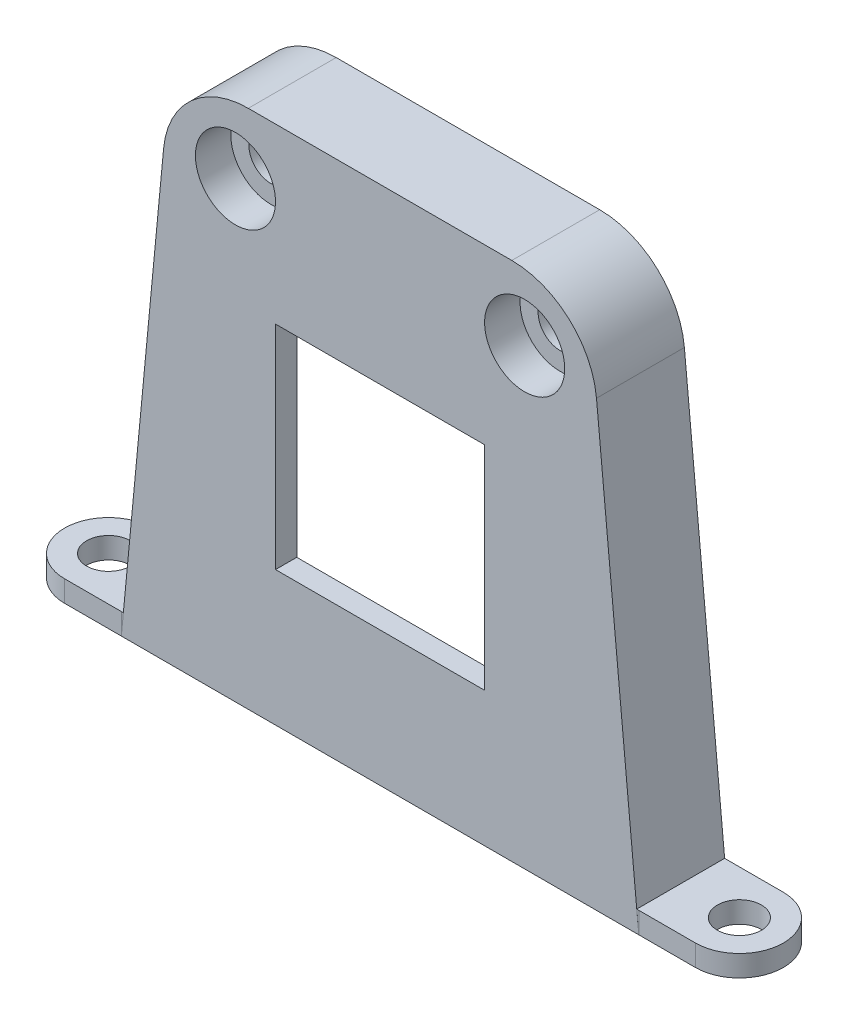
SolidWorks part; units mm, degrees
ref_plane "Přední rovina" through (0, 0, 0) normal (0, 0, 1) x (1, 0, 0)
ref_plane "Horní rovina" through (0, 0, 0) normal (0, 1, 0) x (1, 0, 0)
ref_plane "Pravá rovina" through (0, 0, 0) normal (1, 0, 0) x (0, 0, -1)
sketch "Sketch1" plane through (0, 0, 0) normal (0, 0, 1) x (1, 0, 0)
  line L0 (-12.25, 17.11) -> (12.25, -17.11) construction
  line L16 (18.25, -17.11) -> (15.2676, 14.1793)
  line L17 (9.2947, 19.61) -> (-9.2947, 19.61)
  line L18 (-15.2676, 14.1793) -> (-18.25, -17.11)
  line L19 (-18.25, -17.11) -> (-12.25, -17.11)
  line L20 (-12.25, -17.11) -> (-12.25, 17.11)
  line L21 (-12.25, 17.11) -> (12.25, 17.11)
  line L22 (12.25, 17.11) -> (12.25, -17.11)
  line L23 (12.25, -17.11) -> (18.25, -17.11)
  arc A4 (15.2676, 14.1793) -> (9.2947, 19.61) centre (9.2947, 13.61) ccw
  arc A5 (-9.2947, 19.61) -> (-15.2676, 14.1793) centre (-9.2947, 13.61) ccw
  dimension "D8" = 6
  dimension "D9" = 6
  dimension "D1" = 6
  dimension "D2" = 6
  dimension "D3" = 2.9553
  dimension "D4" = 2.9553
  dimension "D5" = 34.22
  dimension "D6" = 34.22
  dimension "D7" = 42.0863
  dimension "D10" = 2.5
  dimension "D11" = 2.9307
  dimension "D12" = 2.9307
  dimension "D13" = 3.0176
  dimension "D14" = 3.0176
extrude "Boss-Extrude1" add sketch "Sketch1" along normal blind 4.7
sketch "Sketch2" plane through (0, 0, 4.7) normal (0, 0, 1) x (1, 0, 0)
  line L1 (-12.25, -17.11) -> (12.25, -17.11)
  line L2 (-12.25, -17.11) -> (-12.25, 17.11)
  line L3 (-12.25, 17.11) -> (12.25, 17.11)
  line L4 (12.25, -17.11) -> (12.25, 17.11)
  line L5 (-12.25, -17.11) -> (12.25, 17.11) construction
  line L6 (-12.25, 17.11) -> (12.25, -17.11) construction
  line L7 (-7.375, 7.39) -> (7.375, 7.39)
  line L8 (12.25, -17.11) -> (18.25, -17.11)
  line L9 (18.25, -17.11) -> (15.2676, 14.1793)
  line L10 (9.2947, 19.61) -> (-9.2947, 19.61)
  line L11 (-15.2676, 14.1793) -> (-18.25, -17.11)
  line L12 (-18.25, -17.11) -> (-12.25, -17.11)
  line L13 (-12.25, -17.11) -> (-12.25, 17.11)
  line L14 (-12.25, 17.11) -> (12.25, 17.11)
  line L15 (12.25, 17.11) -> (12.25, -17.11)
  line L16 (12.25, -17.11) -> (18.25, -17.11)
  line L17 (18.25, -17.11) -> (15.2676, 14.1793)
  line L18 (9.2947, 19.61) -> (-9.2947, 19.61)
  line L19 (-15.2676, 14.1793) -> (-18.25, -17.11)
  line L20 (-18.25, -17.11) -> (-12.25, -17.11)
  line L21 (-12.25, -17.11) -> (-12.25, 17.11)
  line L22 (-12.25, 17.11) -> (12.25, 17.11)
  line L23 (12.25, 17.11) -> (12.25, -17.11)
  line L24 (-7.375, 7.39) -> (-7.375, -7.61)
  line L25 (-7.375, -7.61) -> (7.375, -7.61)
  line L26 (7.375, 7.39) -> (7.375, -7.61)
  line L27 (-7.375, 7.39) -> (7.375, -7.61) construction
  line L28 (-7.375, -7.61) -> (7.375, 7.39) construction
  arc A2 (15.2676, 14.1793) -> (9.2947, 19.61) centre (9.2947, 13.61) ccw
  arc A3 (-9.2947, 19.61) -> (-15.2676, 14.1793) centre (-9.2947, 13.61) ccw
  arc A4 (15.2676, 14.1793) -> (9.2947, 19.61) centre (9.2947, 13.61) ccw
  arc A5 (-9.2947, 19.61) -> (-15.2676, 14.1793) centre (-9.2947, 13.61) ccw
  point P4 (0, 0)
  point P7 (0, -0.11)
  line M19 (12.25, -17.11) -> (18.25, -17.11)
  line M20 (18.25, -17.11) -> (15.2676, 14.1793)
  arc M21 (15.2676, 14.1793) -> (9.2947, 19.61) centre (9.2947, 13.61) ccw
  line M22 (9.2947, 19.61) -> (-9.2947, 19.61)
  arc M23 (-9.2947, 19.61) -> (-15.2676, 14.1793) centre (-9.2947, 13.61) ccw
  line M24 (-15.2676, 14.1793) -> (-18.25, -17.11)
  line M25 (-18.25, -17.11) -> (-12.25, -17.11)
  line M26 (-12.25, -17.11) -> (-12.25, 17.11)
  line M27 (-12.25, 17.11) -> (12.25, 17.11)
  line M28 (12.25, 17.11) -> (12.25, -17.11)
  dimension "D2" = 15
  dimension "D3" = 14.75
  dimension "D4" = 9.5
  dimension "D1" = 0
extrude "Boss-Extrude2" add sketch "Sketch2" along normal blind 1.5 contours L1 L7 L26 L25 L24 M26 M28 M27 | M28 M19 M20 M21 M22 M23 M24 M25 M26 M27
sketch "Sketch4" plane through (0, 0, 4.7) normal (0, 0, -1) x (-1, 0, 0)
  line L3 (-12.25, 17.11) -> (-12.25, -17.11) construction
  line L4 (12.25, 17.11) -> (-12.25, 17.11) construction
  line L10 (-12.25, 17.11) -> (-7.25, 17.11)
  line L11 (-12.25, 17.11) -> (-12.25, 12.01)
  line L12 (-12.25, 12.01) -> (-8.75, 12.01)
  line L13 (-7.25, 17.11) -> (-7.25, 13.51)
  circle A0 centre (-10.2, 14.86) radius 1.55
  arc A3 (-8.75, 12.01) -> (-7.25, 13.51) centre (-8.75, 13.51) ccw
  point P14 (-7.25, 12.01)
  dimension "D1" = 3.1
  dimension "D5" = 5.1
  dimension "D4" = 5
  dimension "D6" = 1.5
  dimension "D2" = 2.05
  dimension "D3" = 2.25
extrude "Boss-Extrude3" add sketch "Sketch4" along normal blind 3.5
sketch "Sketch5" plane through (0, 0, 4.7) normal (0, 0, -1) x (-1, 0, 0)
  circle A0 centre (-10.2, 14.86) radius 1.55
  circle A2 centre (-10.2, 14.86) radius 1.55 construction
extrude "Cut-Extrude1" cut sketch "Sketch5" against normal through all
sketch "Sketch6" plane through (0, 0, 6.2) normal (0, 0, 1) x (1, 0, 0)
  circle A0 centre (10.2, 14.86) radius 2.825
  dimension "D1" = 5.65
extrude "Cut-Extrude2" cut sketch "Sketch6" against normal blind 2.5
sketch "Sketch7" plane through (0, -17.11, 0) normal (0, -1, 0) x (1, 0, 0)
  line L0 (-22.25, 3.1) -> (-18.25, 3.1) construction
  line L1 (-18.25, 6.2) -> (-18.25, 0) construction
  line L2 (-22.25, 6.2) -> (-18.25, 6.2)
  line L3 (-22.25, 0) -> (-18.25, 0)
  line L5 (-18.25, 6.2) -> (18.25, 6.2) construction
  arc A0 (-22.25, 6.2) -> (-22.25, 0) centre (-22.25, 3.1) ccw
  arc A1 (-18.25, 0) -> (-18.25, 6.2) centre (-18.25, 3.1) ccw
  circle A2 centre (-22.25, 3.1) radius 1.55
  point P4 (-20.25, 3.1)
  dimension "D3" = 3.1
  dimension "D2" = 4
extrude "Boss-Extrude4" add sketch "Sketch7" against normal blind 1.5
mirror "Mirror1" about plane through (0, 0, 0) normal (1, 0, 0) of "Boss-Extrude4", "Boss-Extrude3", "Cut-Extrude2"
